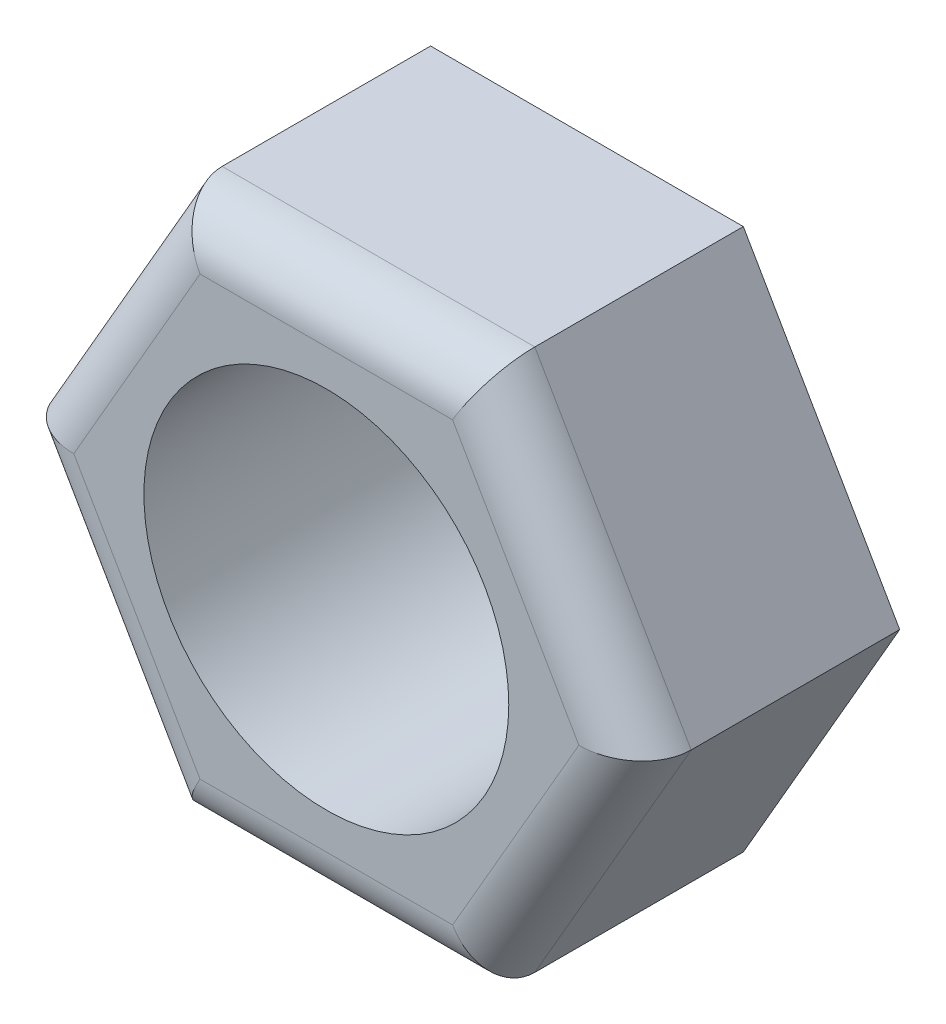
SolidWorks part; units mm, degrees
ref_plane "正面" through (0, 0, 0) normal (0, 0, 1) x (1, 0, 0)
ref_plane "平面" through (0, 0, 0) normal (0, 1, 0) x (1, 0, 0)
ref_plane "右側面" through (0, 0, 0) normal (1, 0, 0) x (0, 0, -1)
sketch "ｽｹｯﾁ1" plane through (0, 0, 0) normal (0, 0, 1) x (1, 0, 0)
  line L1 (3, 0) -> (1.5, 2.5981)
  line L2 (1.5, 2.5981) -> (-1.5, 2.5981)
  line L3 (-1.5, 2.5981) -> (-3, 0)
  line L4 (-3, 0) -> (-1.5, -2.5981)
  line L5 (-1.5, -2.5981) -> (1.5, -2.5981)
  line L6 (1.5, -2.5981) -> (3, 0)
  circle A0 centre (0, 0) radius 2.5981 construction
  circle A1 centre (0, 0) radius 1.75
extrude "ﾎﾞｽ - 押し出し1" add sketch "ｽｹｯﾁ1" along normal blind 2.5
fillet "ﾌｨﾚｯﾄ1" radius 0.5 6 edges at (-2.25, 1.299, 2.5) (-2.25, -1.299, 2.5) (0, -2.5981, 2.5) (2.25, -1.299, 2.5) (2.25, 1.299, 2.5) (0, 2.5981, 2.5)
